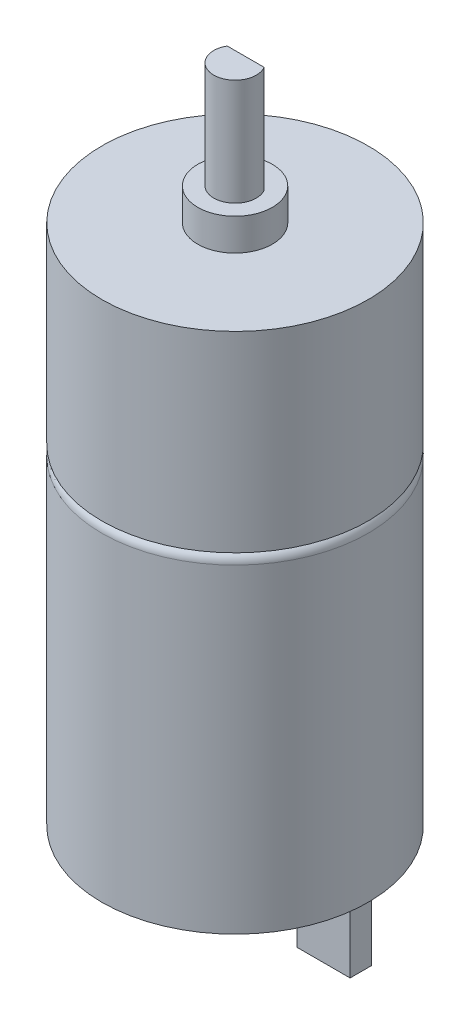
SolidWorks part; units mm, degrees
ref_plane "Plano frontal" through (0, 0, 0) normal (0, 0, 1) x (1, 0, 0)
ref_plane "Plano superior" through (0, 0, 0) normal (0, 1, 0) x (1, 0, 0)
ref_plane "Plano direito" through (0, 0, 0) normal (1, 0, 0) x (0, 0, -1)
sketch "Esboço1" plane through (0, 0, 0) normal (0, 1, 0) x (1, 0, 0)
  circle A0 centre (0, 0) radius 12.5
  dimension "D1" = 25
extrude "Ressalto-extrusão1" add sketch "Esboço1" along normal blind 31
fillet "Filete1" radius 1 1 edges at (0, 31, 12.5)
sketch "Esboço2" plane through (0, 31, 0) normal (0, 1, 0) x (1, 0, 0)
  circle A0 centre (0, 0) radius 12.5
extrude "Ressalto-extrusão2" add sketch "Esboço2" along normal blind 18
sketch "Esboço3" plane through (0, 0, 0) normal (0, -1, 0) x (1, 0, 0)
  line L0 (0, 12.5) -> (0, -12.5) construction
  line L1 (0, 0) -> (-12.5, 0) construction
  line L2 (11.8, 1) -> (6.8, 1)
  line L3 (-11.8, -1) -> (-6.8, -1)
  line L4 (-11.8, -1) -> (-11.8, 1)
  line L5 (-11.8, 1) -> (-6.8, 1)
  line L6 (-6.8, -1) -> (-6.8, 1)
  line L7 (-11.8, -1) -> (-6.8, 1) construction
  line L8 (-11.8, 1) -> (-6.8, -1) construction
  line L9 (6.8, -1) -> (6.8, 1)
  line L10 (11.8, -1) -> (6.8, -1)
  line L11 (11.8, -1) -> (11.8, 1)
  circle A0 centre (0, 0) radius 12.5 construction
  point P8 (-9.3, 0)
  dimension "D1" = 5
  dimension "D2" = 2
  dimension "D3" = 3.2
extrude "Ressalto-extrusão3" add sketch "Esboço3" along normal blind 6
sketch "Esboço5" plane through (0, 49, 0) normal (0, 1, 0) x (1, 0, 0)
  circle A0 centre (0, 0) radius 3.5
  dimension "D1" = 7
extrude "Ressalto-extrusão4" add sketch "Esboço5" along normal blind 3
sketch "Esboço6" plane through (0, 52, 0) normal (0, 1, 0) x (1, 0, 0)
  line L0 (0, -2) -> (0, 2) construction
  line L1 (1.7321, 1) -> (-1.7321, 1)
  circle A0 centre (0, 0) radius 2
  point P8 (0, 1)
  dimension "D1" = 4
  dimension "D2" = 3
extrude "Ressalto-extrusão5" add sketch "Esboço6" along normal blind 10 contours L0 A0 L1 | A0 L0 L1
